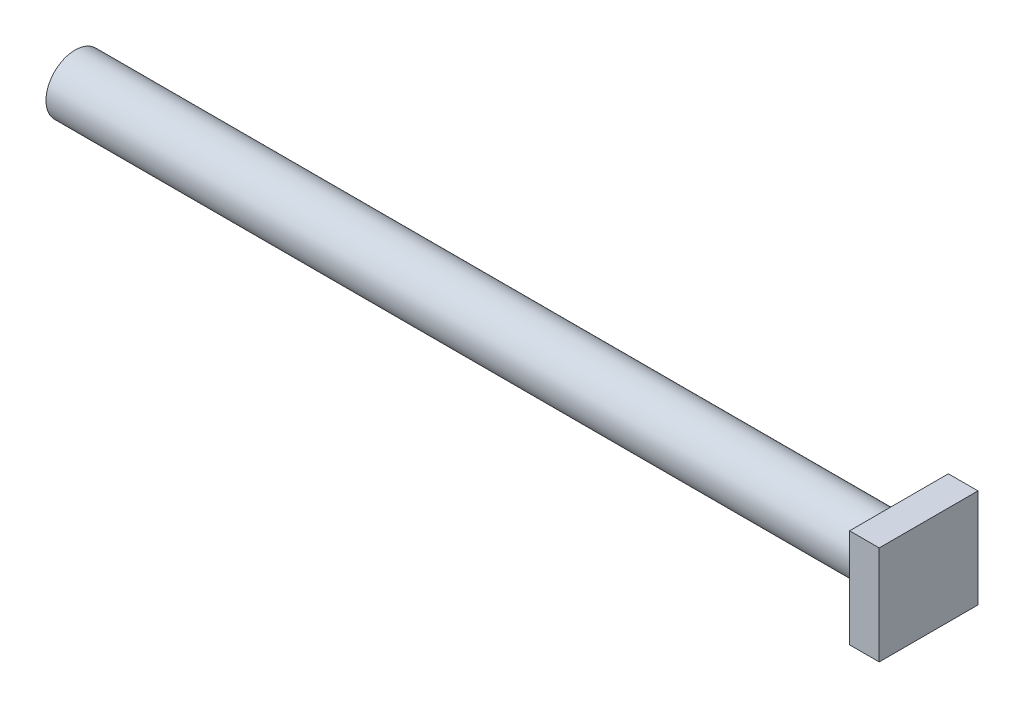
SolidWorks part; units mm, degrees
ref_plane "Front Plane" through (0, 0, 0) normal (0, 0, 1) x (1, 0, 0)
ref_plane "Top Plane" through (0, 0, 0) normal (0, 1, 0) x (1, 0, 0)
ref_plane "Right Plane" through (0, 0, 0) normal (1, 0, 0) x (0, 0, -1)
sketch "Sketch3" plane through (0, 0, 0) normal (1, 0, 0) x (0, 0, -1)
  circle A0 centre (0, 0) radius 2.95
  dimension "D1" = 5.9
extrude "Boss-Extrude1" add sketch "Sketch3" against normal blind 83.4 contours A0
sketch "Sketch4" plane through (0, 0, 0) normal (1, 0, 0) x (0, 0, -1)
  line L1 (-5, -5) -> (5, -5)
  line L2 (-5, -5) -> (-5, 5)
  line L3 (-5, 5) -> (5, 5)
  line L4 (5, -5) -> (5, 5)
  line L5 (-5, -5) -> (5, 5) construction
  line L6 (-5, 5) -> (5, -5) construction
  point P0 (0, 0)
  dimension "D1" = 10
extrude "Boss-Extrude2" add sketch "Sketch4" along normal blind 3
